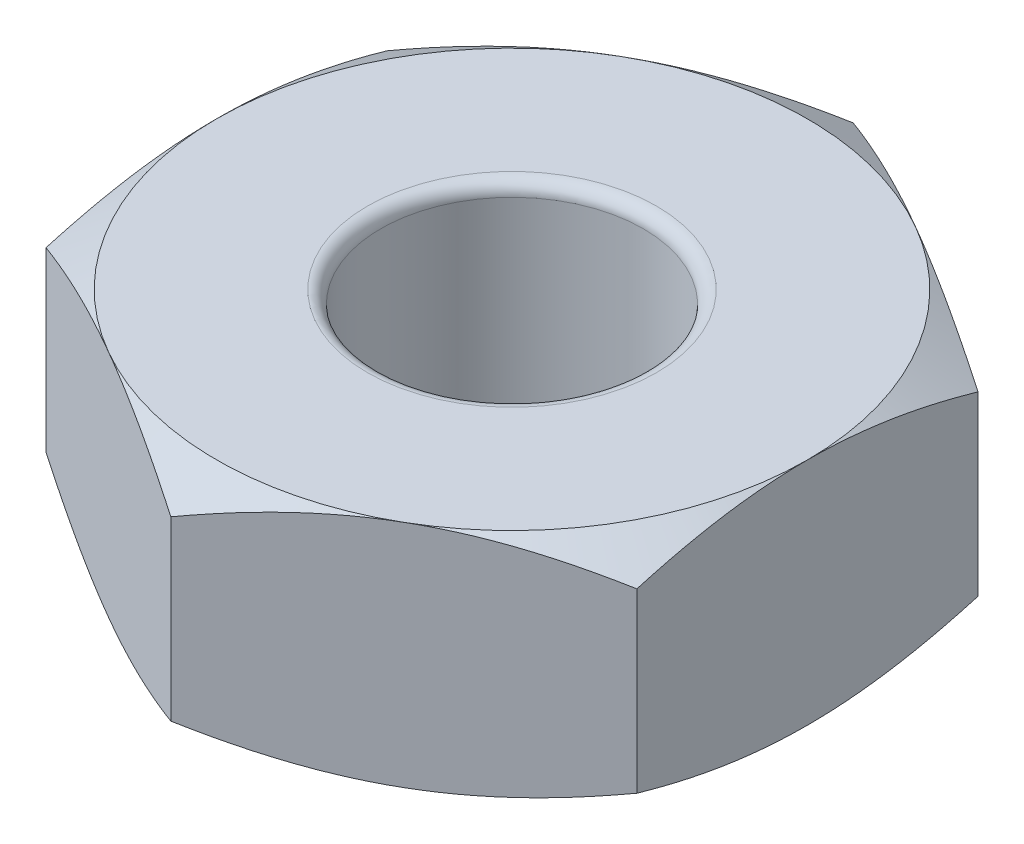
SolidWorks part; units mm, degrees
ref_plane "Front Plane" through (0, 0, 0) normal (0, 0, 1) x (1, 0, 0)
ref_plane "Top Plane" through (0, 0, 0) normal (0, 1, 0) x (1, 0, 0)
ref_plane "Right Plane" through (0, 0, 0) normal (1, 0, 0) x (0, 0, -1)
sketch "Sketch1" plane through (0, 0, 0) normal (0, 1, 0) x (1, 0, 0)
  line L1 (0, -2.5981) -> (2.25, -1.299)
  line L2 (2.25, -1.299) -> (2.25, 1.299)
  line L3 (2.25, 1.299) -> (0, 2.5981)
  line L4 (0, 2.5981) -> (-2.25, 1.299)
  line L5 (-2.25, 1.299) -> (-2.25, -1.299)
  line L6 (-2.25, -1.299) -> (0, -2.5981)
  circle A0 centre (0, 0) radius 1
  circle A1 centre (0, 0) radius 2.25 construction
  dimension "D1" = 2
  dimension "D2" = 4.5
extrude "Boss-Extrude1" add sketch "Sketch1" along normal blind 1.75
sketch "Sketch2" plane through (0, 1.75, 0) normal (0, 1, 0) x (1, 0, 0)
  circle A0 centre (0, 0) radius 2.25 construction
  circle A1 centre (0, 0) radius 2.25
extrude "Cut-Extrude1" cut sketch "Sketch2" against normal blind 1.75 draft 60 flip side to cut
sketch "Sketch3" plane through (0, 0, 0) normal (0, -1, 0) x (1, 0, 0)
  circle A0 centre (0, 0) radius 2.25 construction
  circle A1 centre (0, 0) radius 2.25
extrude "Cut-Extrude2" cut sketch "Sketch3" against normal blind 1.75 draft 60 flip side to cut
fillet "Fillet1" radius 0.1 2 edges at (0, 0, 1) (0, 1.75, 1)
